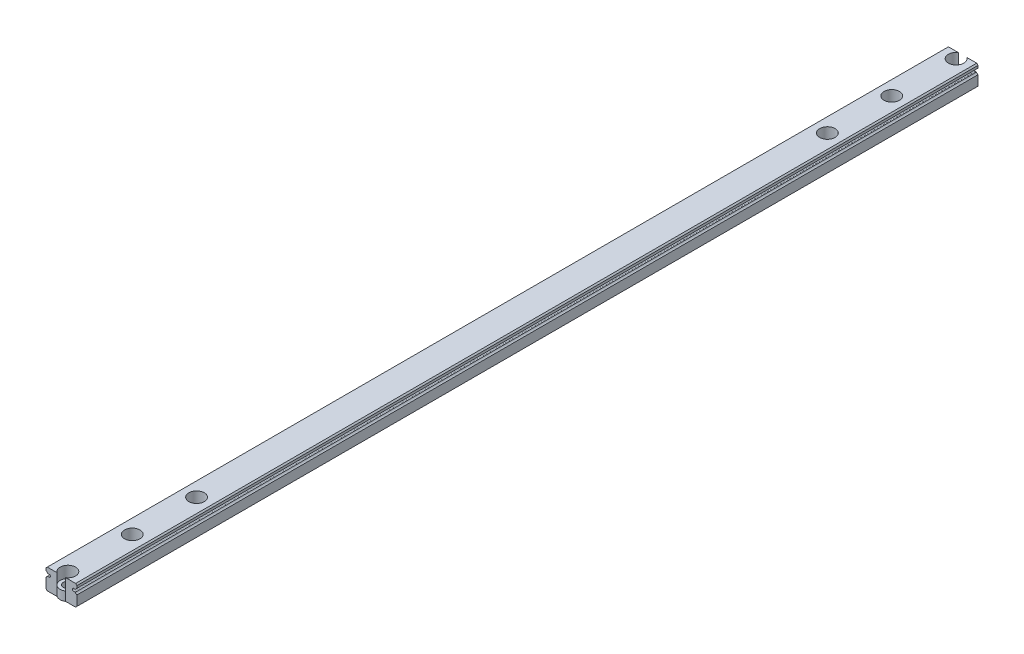
SolidWorks part; units mm, degrees
material "Chrome Stainless Steel"
ref_plane "Front Plane" through (0, 0, 0) normal (0, 0, 1) x (1, 0, 0)
ref_plane "Top Plane" through (0, 0, 0) normal (0, 1, 0) x (1, 0, 0)
ref_plane "Right Plane" through (0, 0, 0) normal (1, 0, 0) x (0, 0, -1)
sketch "Sketch1" plane through (0, 0, 0) normal (0, 0, 1) x (1, 0, 0)
  line L0 (0, 4) -> (0, -4) construction
  line L1 (5.5, -4) -> (-5.5, -4)
  line L2 (-5.5, -4) -> (-6, -3.5)
  line L3 (-6, -3.5) -> (-6, 0.3689)
  line L4 (5.5, 4) -> (-5.5, 4)
  line L5 (-5.5, 4) -> (-6, 3.5)
  line L6 (-6, 2.5511) -> (-6, 3.5)
  line L7 (-5.3839, 0.985) -> (-4.9211, 0.985)
  line L8 (-5.3839, 1.935) -> (-4.9211, 1.935)
  line L9 (5.3839, 0.985) -> (4.9211, 0.985)
  line L10 (5.5, 4) -> (6, 3.5)
  line L11 (6, 2.5511) -> (6, 3.5)
  line L12 (5.3839, 1.935) -> (4.9211, 1.935)
  line L13 (6, -3.5) -> (6, 0.3689)
  line L14 (5.5, -4) -> (6, -3.5)
  circle A0 centre (-6.475, 1.46) radius 1.19 construction
  circle A1 centre (-4.765, 1.46) radius 0.5 construction
  arc A2 (-6, 0.3689) -> (-5.3839, 0.985) centre (-6.475, 1.46) ccw
  arc A3 (-5.3839, 1.935) -> (-6, 2.5511) centre (-6.475, 1.46) ccw
  arc A4 (-4.9211, 0.985) -> (-4.9211, 1.935) centre (-4.765, 1.46) ccw
  arc A5 (5.3839, 1.935) -> (6, 2.5511) centre (6.475, 1.46) cw
  arc A6 (4.9211, 0.985) -> (4.9211, 1.935) centre (4.765, 1.46) cw
  arc A7 (6, 0.3689) -> (5.3839, 0.985) centre (6.475, 1.46) cw
  point P4 (0, 0)
  dimension "D5" = 5.46
  dimension "D6" = 6.475
  dimension "D7" = 2.38
  dimension "D11" = 1
  dimension "D12" = 5.46
  dimension "D13" = 4.765
  dimension "D1" = 8
  dimension "D2" = 0.5
  dimension "D3" = 0.5
  dimension "D4" = 6
  dimension "D8" = 0.5
  dimension "D9" = 0.5
  dimension "D10" = 6
  dimension "D14" = 0.475
  dimension "D15" = 0.475
extrude "Boss-Extrude1" add sketch "Sketch1" along normal blind 420 contours L13 A7 L9 A6 L12 A5 L11 L10 L4 L5 L6 A3 L8 A4 L7 A2 L3 L2 L1 L14
sketch "Sketch2" plane through (0, 4, 0) normal (0, 1, 0) x (1, 0, 0)
  line L0 (5.5, 0) -> (-5.5, 0) construction
  circle A0 centre (0, -12.5) radius 3
  dimension "D1" = 12.5
extrude "Cut-Extrude1" cut sketch "Sketch2" against normal blind 4.5
sketch "Sketch3" plane through (0, -0.5, 0) normal (0, 1, 0) x (1, 0, 0)
  circle A0 centre (0, -12.5) radius 1.75
extrude "Cut-Extrude2" cut sketch "Sketch3" against normal through all
pattern_linear "LPattern1" count 4 spacing 25 along (0, 0, 1) of "Cut-Extrude1", "Cut-Extrude2"
sketch "Sketch4" plane through (0, 4, 0) normal (0, 1, 0) x (1, 0, 0)
  line L0 (-6, -420) -> (-6, 0) construction
  point P0 (-6, -210)
ref_plane "Plane1" through (0, 0, 210) normal (0, 0, 1) x (1, 0, 0)
mirror "Mirror1" about plane through (0, 0, 210) normal (0, 0, 1) of "LPattern1", "Cut-Extrude2", "Cut-Extrude1"
sketch "Sketch5" plane through (0, 4, 0) normal (0, 1, 0) x (1, 0, 0)
  line L0 (-6, -385) -> (6, -385)
  line L1 (6, 0) -> (-6, 0)
  line L2 (6, 0) -> (6, -420)
  line L3 (6, -420) -> (-6, -420)
  line L4 (-6, 0) -> (-6, -420)
  line L5 (-4.4, -210) -> (4.4, -210) construction
  line L6 (-6, -35) -> (6, -35)
  circle M6 centre (0, -382.5) radius 3
  circle M9 centre (0, -407.5) radius 3
  circle M12 centre (0, -37.5) radius 3
  circle M13 centre (0, -12.5) radius 3
  line M14 (5.5, 0) -> (-5.5, 0)
  line M15 (-5.5, 0) -> (-5.5, -420)
  line M16 (-5.5, -420) -> (5.5, -420)
  line M17 (5.5, -420) -> (5.5, 0)
  dimension "D1" = 35
extrude "Cut-Extrude3" cut sketch "Sketch5" against normal through all contours L0 M15 M16 M17 M6 M9 | L0 L4 L3 M15 | L3 L2 L0 M17 | M9 | L6 M15 M12 M17 M14 M13 | M13 | L6 L2 L1 M17 | L4 L6 L1 M15
